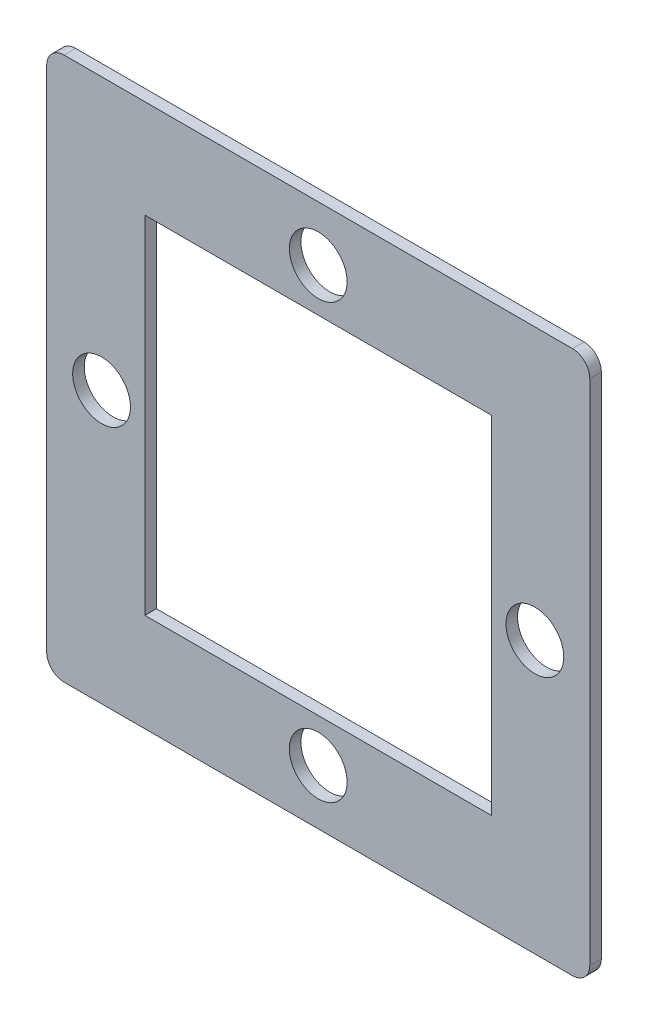
SolidWorks part; units mm, degrees
ref_plane "Front Plane" through (0, 0, 0) normal (0, 0, 1) x (1, 0, 0)
ref_plane "Top Plane" through (0, 0, 0) normal (0, 1, 0) x (1, 0, 0)
ref_plane "Right Plane" through (0, 0, 0) normal (1, 0, 0) x (0, 0, -1)
sketch "Sketch1" plane through (0, 0, 0) normal (0, 0, 1) x (1, 0, 0)
  line L1 (0, 0) -> (47, 0)
  line L2 (0, 0) -> (0, 47)
  line L3 (0, 47) -> (47, 47)
  line L4 (47, 0) -> (47, 47)
  line L5 (8.5, 38.5) -> (38.5, 38.5)
  line L6 (8.5, 38.5) -> (8.5, 8.5)
  line L7 (8.5, 8.5) -> (38.5, 8.5)
  line L8 (38.5, 38.5) -> (38.5, 8.5)
  circle A0 centre (23.5, 4.75) radius 2.5
  circle A1 centre (42.25, 23.5) radius 2.5
  circle A2 centre (23.5, 42.25) radius 2.5
  circle A3 centre (4.75, 23.5) radius 2.5
  point P17 (23.5, 47)
  point P18 (0, 0)
  point P19 (0, 0)
  dimension "D7" = 5
  dimension "D8" = 5
  dimension "D9" = 5
  dimension "D10" = 5
  dimension "D1" = 47
  dimension "D2" = 47
  dimension "D3" = 30
  dimension "D4" = 30
  dimension "D5" = 8.5
  dimension "D6" = 8.5
  dimension "D11" = 4.75
  dimension "D12" = 4.75
  dimension "D13" = 4.75
  dimension "D14" = 4.75
  dimension "D15" = 23.5
  dimension "D16" = 23.5
extrude "Boss-Extrude1" add sketch "Sketch1" along normal blind 1
fillet "Fillet1" radius 1.5 4 edges at (0, 0, 0.5) (47, 0, 0.5) (47, 47, 0.5) (0, 47, 0.5)
